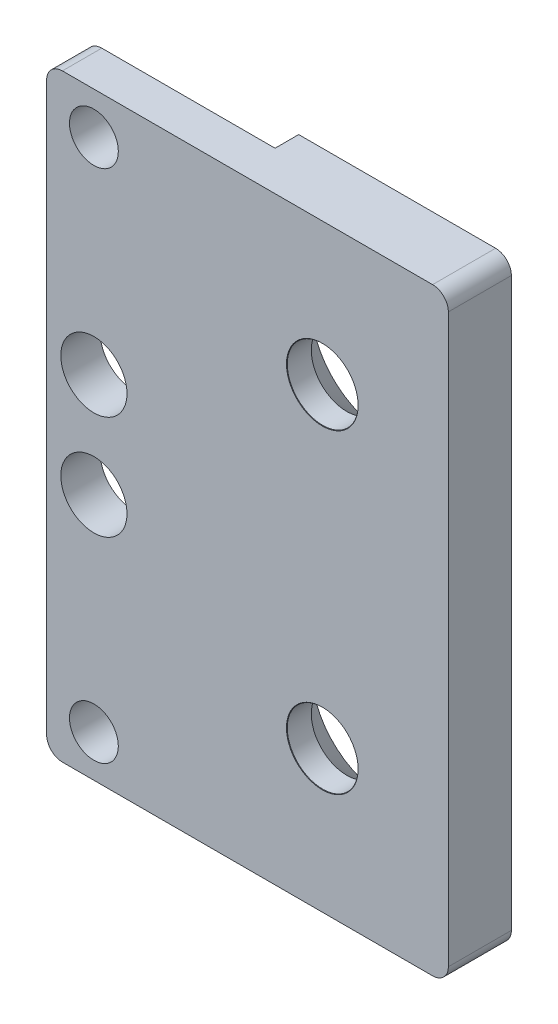
SolidWorks part; units mm, degrees
material "ABS"
ref_plane "Front Plane" through (0, 0, 0) normal (0, 0, 1) x (1, 0, 0)
ref_plane "Top Plane" through (0, 0, 0) normal (0, 1, 0) x (1, 0, 0)
ref_plane "Right Plane" through (0, 0, 0) normal (1, 0, 0) x (0, 0, -1)
sketch "Sketch1" plane through (0, 0, 0) normal (0, 0, 1) x (1, 0, 0)
  line L1 (12.75, -19) -> (-12.75, -19)
  line L2 (12.75, -19) -> (12.75, 19)
  line L3 (12.75, 19) -> (-12.75, 19)
  line L4 (-12.75, -19) -> (-12.75, 19)
  line L5 (12.75, -19) -> (-12.75, 19) construction
  line L6 (12.75, 19) -> (-12.75, -19) construction
  point P0 (0, 0)
  dimension "D1" = 38
  dimension "D2" = 25.5
extrude "Boss-Extrude1" add sketch "Sketch1" along normal blind 4
sketch "Sketch2" plane through (0, 19, 0) normal (0, 1, 0) x (1, 0, 0)
  line L0 (12.75, -4) -> (-12.75, -4) construction
  line L1 (-12.75, 0) -> (-0.75, 0)
  line L2 (-12.75, 0) -> (-12.75, -1.5)
  line L3 (-12.75, -1.5) -> (-0.75, -1.5)
  line L4 (-0.75, 0) -> (-0.75, -1.5)
  dimension "D1" = 2.5
  dimension "D2" = 12
extrude "Cut-Extrude1" cut sketch "Sketch2" against normal up to next
hole_wizard "CSK for M4 Countersunk Flat Head Screw1" positions "Sketch3" profile "Sketch5" countersink size "M4" standard "DIN" end condition up to next
sketch "Sketch3" plane through (0, 0, 0) normal (0, 0, -1) x (-1, 0, 0)
  line L0 (-12.75, 0) -> (0.75, 0) construction
  line L1 (-12.75, -19) -> (-12.75, 19) construction
  line L2 (0.75, -19) -> (0.75, 19) construction
  line L4 (-4.75, 0) -> (-4.75, 15) construction
  point P0 (-4.75, 10)
  point P2 (-4.75, -10)
  dimension "D1" = 20
  dimension "D2" = 8
sketch "Sketch5" plane through (4.75, 10, 0) normal (1, 0, 0) x (0, 1, 0)
  line L0 (0, 0) -> (0, 4)
  line L1 (0, 4) -> (2.275, 4)
  line L2 (2.25, 3.975) -> (2.25, 2.45)
  line L3 (2.25, 2.45) -> (4.7, 0)
  line L5 (4.7, 0) -> (0, 0)
  line L6 (-2.25, 2.45) -> (-4.7, 0) construction
  line L7 (2.275, 4) -> (2.25, 3.975)
  line L8 (-2.275, 4) -> (-2.25, 3.975) construction
  line L11 (0, -6.35) -> (0, 107.95) construction
  dimension "Thru Hole Dia." = 4.5
  dimension "Thru Hole Depth" = 4
  dimension "Near C'Sink Dia." = 9.4
  dimension "Near C'Sink Angle" = 90
  dimension "Far C'Sink Dia." = 4.55
  dimension "Far C'Sink Angle" = 90
hole_wizard "M3 Clearance Hole1" positions "Sketch8" profile "Sketch10" hole size "M3" standard "DIN" end condition up to next
sketch "Sketch8" plane through (0, 0, 1.5) normal (0, 0, -1) x (-1, 0, 0)
  line L2 (0.75, -19) -> (12.75, -19) construction
  line L3 (12.75, -19) -> (12.75, 19) construction
  line L4 (12.75, 0) -> (0, 0) construction
  line L5 (12.75, -19) -> (12.75, 19) construction
  point P0 (9.75, -16.35)
  point P18 (9.75, 16.35)
  dimension "D1" = 2.65
  dimension "D2" = 3
sketch "Sketch10" plane through (-9.75, -16.35, 1.5) normal (1, 0, 0) x (0, 1, 0)
  line L0 (0, 0) -> (0, 2.5)
  line L1 (0, 2.5) -> (1.55, 2.5)
  line L2 (1.55, 2.5) -> (1.55, 0)
  line L5 (1.55, 0) -> (0, 0)
  line L11 (0, -6.35) -> (0, 107.95) construction
  dimension "Thru Hole Dia." = 3.1
  dimension "Thru Hole Depth" = 2.5
hole_wizard "Hole1" positions "Sketch11" profile "Sketch13" legacy end condition up to next
sketch "Sketch11" plane through (0, 0, 1.5) normal (0, 0, -1) x (-1, 0, 0)
  line L2 (0.75, -19) -> (12.75, -19) construction
  line L3 (12.75, -19) -> (12.75, 19) construction
  line L4 (0, 0) -> (12.75, 0) construction
  line L5 (12.75, -19) -> (12.75, 19) construction
  point P0 (9.75, -3.3)
  point P22 (9.75, 3.3)
  dimension "D1" = 15.7
  dimension "D2" = 3
sketch "Sketch13" plane through (-9.75, -3.3, 1.5) normal (1, 0, 0) x (0, 1, 0)
  line L0 (0, 0) -> (0, 2.5)
  line L1 (0, 2.5) -> (2.1, 2.5)
  line L2 (2.1, 2.5) -> (2.1, 0)
  line L3 (2.1, 0) -> (0, 0)
  line L4 (0, 110) -> (0, -10) construction
  dimension "Diameter" = 4.2
  dimension "Depth" = 2.5
fillet "Fillet1" radius 1 4 edges at (-12.75, -19, 2.75) (-12.75, 19, 2.75) (12.75, 19, 2) (12.75, -19, 2)
